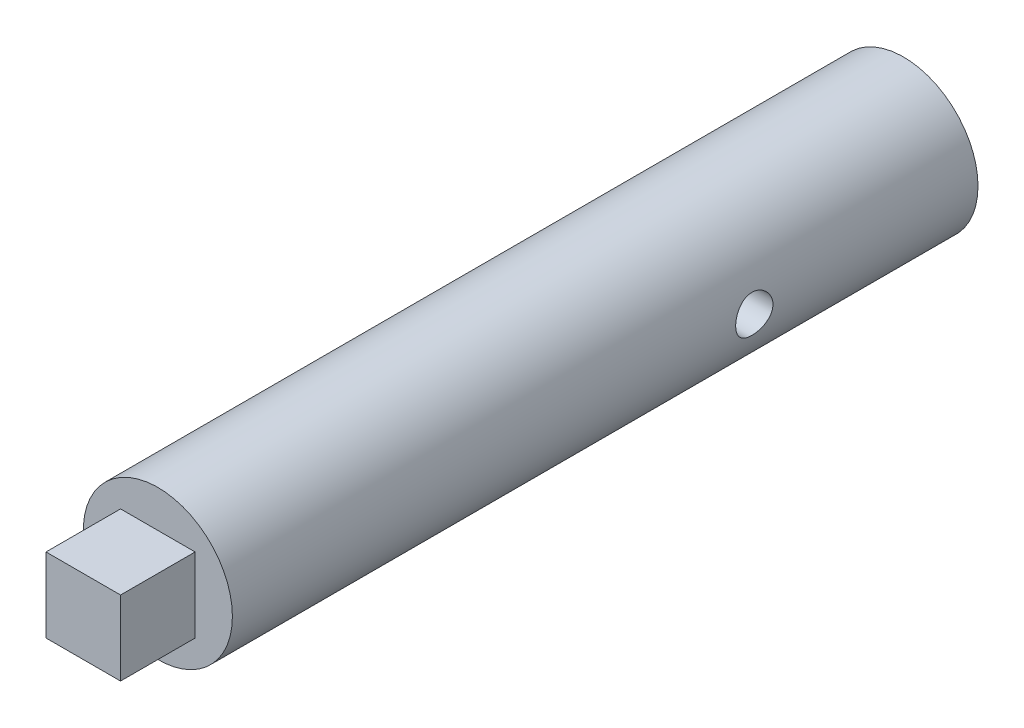
SolidWorks part; units mm, degrees
ref_plane "Plan de face" through (0, 0, 0) normal (0, 0, 1) x (1, 0, 0)
ref_plane "Plan de dessus" through (0, 0, 0) normal (0, 1, 0) x (1, 0, 0)
ref_plane "Plan de droite" through (0, 0, 0) normal (1, 0, 0) x (0, 0, -1)
sketch "Sketch1" plane through (0, 0, 0) normal (0, 0, 1) x (1, 0, 0)
  circle A0 centre (0, 0) radius 5
  dimension "D1" = 10
extrude "Boss-Extrude1" add sketch "Sketch1" along normal blind 50
sketch "Sketch2" plane through (0, 0, 50) normal (0, 0, 1) x (1, 0, 0)
  line L1 (-2.5, -2.5) -> (2.5, -2.5)
  line L2 (-2.5, -2.5) -> (-2.5, 2.5)
  line L3 (-2.5, 2.5) -> (2.5, 2.5)
  line L4 (2.5, -2.5) -> (2.5, 2.5)
  point P4 (2.5, 0)
  point P5 (0, 2.5)
  dimension "D1" = 5
  dimension "D2" = 5
extrude "Boss-Extrude2" add sketch "Sketch2" along normal blind 5
sketch "Sketch5" plane through (0, 0, 0) normal (1, 0, 0) x (0, 0, -1)
  line L0 (-50, 0) -> (-15, 0) construction
  line L1 (-50, 5) -> (-50, -5) construction
  circle A0 centre (-15, 0) radius 1.25
  dimension "D2" = 2.5
  dimension "D1" = 35
extrude "Cut-Extrude1" cut sketch "Sketch5" against normal blind 5 and the other way blind 5
